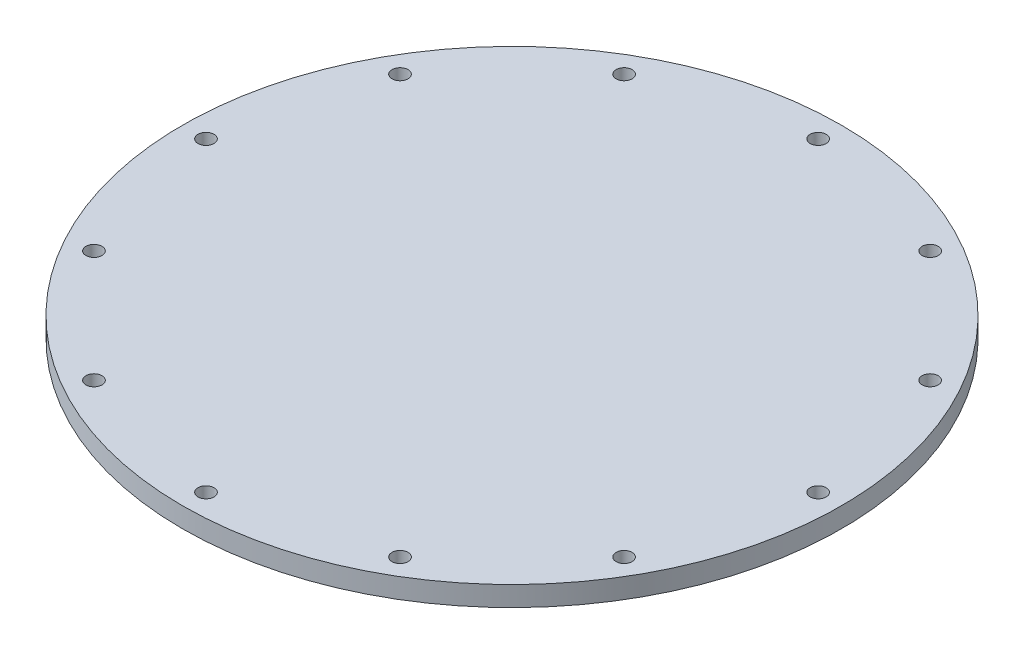
SolidWorks part; units mm, degrees
material "6061-T4 (SS)"
ref_plane "Front Plane" through (0, 0, 0) normal (0, 0, 1) x (1, 0, 0)
ref_plane "Top Plane" through (0, 0, 0) normal (0, 1, 0) x (1, 0, 0)
ref_plane "Right Plane" through (0, 0, 0) normal (1, 0, 0) x (0, 0, -1)
sketch "Sketch1" plane through (0, 0, 0) normal (0, 1, 0) x (1, 0, 0)
  circle A0 centre (0, 0) radius 89.7255
  circle A1 centre (0, 0) radius 104.775
  circle A2 centre (0, 0) radius 81.407
  circle A3 centre (0, -97.2502) radius 2.5527
  circle A4 centre (48.6251, -84.2212) radius 2.5527
  circle A5 centre (-48.6251, -84.2212) radius 2.5527
  circle A6 centre (-84.2212, -48.6251) radius 2.5527
  circle A7 centre (-97.2502, 0) radius 2.5527
  circle A8 centre (-84.2212, 48.6251) radius 2.5527
  circle A9 centre (-48.6251, 84.2212) radius 2.5527
  circle A10 centre (0, 97.2502) radius 2.5527
  circle A11 centre (48.6251, 84.2212) radius 2.5527
  circle A12 centre (84.2212, 48.6251) radius 2.5527
  circle A13 centre (97.2502, 0) radius 2.5527
  circle A14 centre (84.2212, -48.6251) radius 2.5527
  circle A15 centre (0, 0) radius 74.295
  circle A16 centre (0, 0) radius 67.818
  text T0 "SOLIDWORKS Educational Product." font "SWTXT" height 4.8336
  text T1 "For Instructional Use Only." font "SWTXT" height 4.8336
sketch "Sketch2" plane through (0, 0, 0) normal (0, 1, 0) x (1, 0, 0)
  circle A0 centre (0, 0) radius 104.775
  dimension "D1" = 209.55
extrude "Face Plate" add sketch "Sketch2" along normal blind 6.35
sketch "Sketch3" plane through (0, 6.35, 0) normal (0, 1, 0) x (1, 0, 0)
  circle A0 centre (-84.2212, 48.6251) radius 2.5527
  dimension "D1" = 5.1054
extrude "Cut-Extrude1" cut sketch "Sketch3" against normal up to surface (6.35 mm away) up to face at (0, 0, 104.775)
pattern_circular "CirPattern1" count 12 over 360 about axis through (0.05, 0, 0.0289) along (0, 1, 0) of "Cut-Extrude1"
